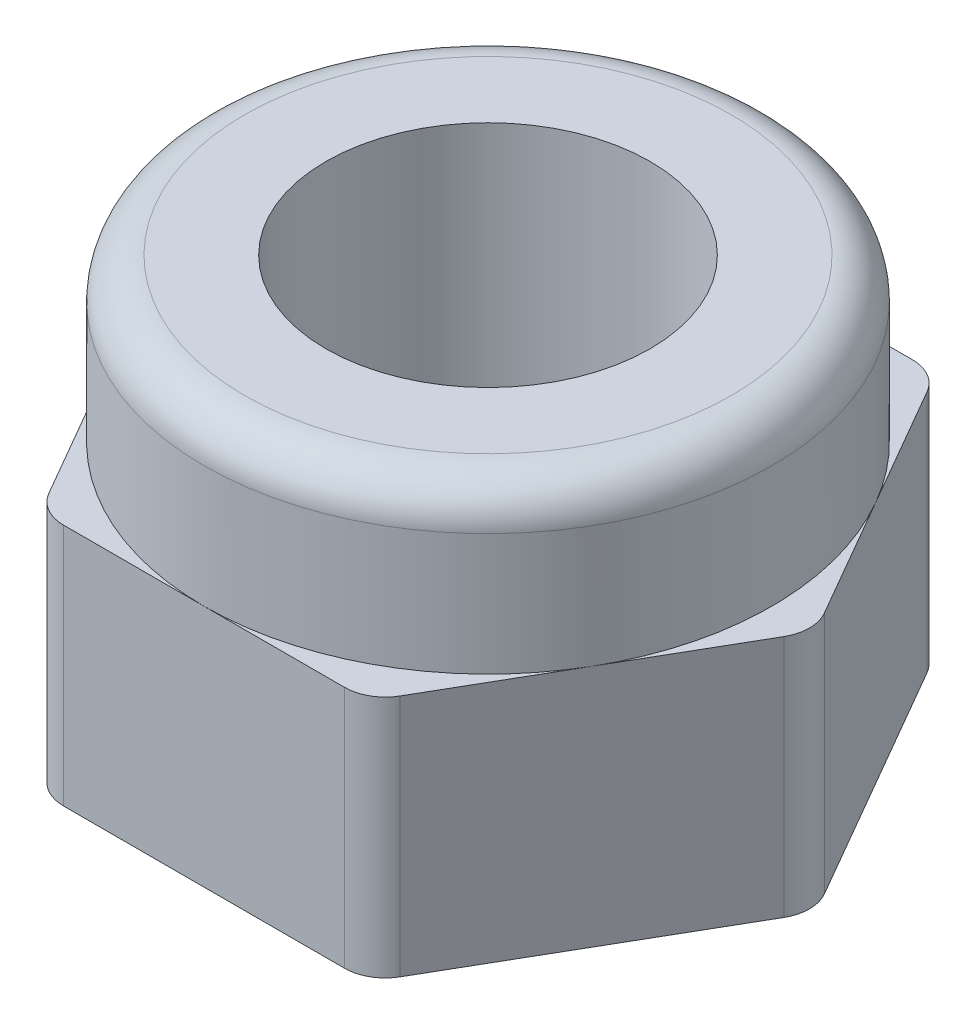
SolidWorks part; units mm, degrees
ref_plane "前视基准面" through (0, 0, 0) normal (0, 0, 1) x (1, 0, 0)
ref_plane "上视基准面" through (0, 0, 0) normal (0, 1, 0) x (1, 0, 0)
ref_plane "右视基准面" through (0, 0, 0) normal (1, 0, 0) x (0, 0, -1)
other "Configuration Table"
sketch "Sketch2" plane through (0, 0, 0) normal (0, 1, 0) x (1, 0, 0)
  line L1 (4.0415, 0) -> (2.0207, 3.5)
  line L2 (2.0207, 3.5) -> (-2.0207, 3.5)
  line L3 (-2.0207, 3.5) -> (-4.0415, 0)
  line L4 (-4.0415, 0) -> (-2.0207, -3.5)
  line L5 (-2.0207, -3.5) -> (2.0207, -3.5)
  line L6 (2.0207, -3.5) -> (4.0415, 0)
  circle A0 centre (0, 0) radius 3.5 construction
  circle A1 centre (0, 0) radius 2
  dimension "D1" = 7
extrude "Boss-Extrude1" add sketch "Sketch2" along normal blind 3
sketch "Sketch6" plane through (0, 3, 0) normal (0, 1, 0) x (1, 0, 0)
  circle A0 centre (0, 0) radius 3.5
  circle A1 centre (0, 0) radius 2
extrude "Boss-Extrude2" add sketch "Sketch6" along normal blind 2
fillet "Fillet1" radius 0.5 1 edges at (0, 5, 3.5)
fillet "Fillet4" radius 0.5 6 edges at (-2.0207, 1.5, 3.5) (-4.0415, 1.5, 0) (-2.0207, 1.5, -3.5) (2.0207, 1.5, -3.5) (4.0415, 1.5, 0) (2.0207, 1.5, 3.5)
